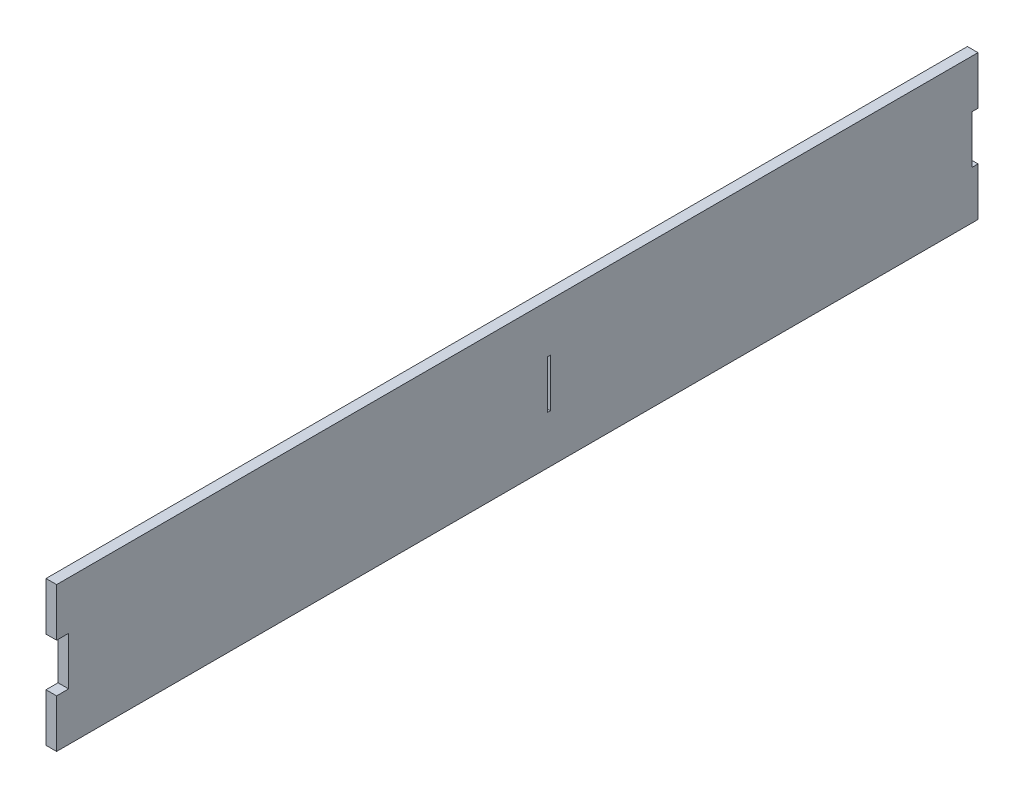
SolidWorks part; units mm, degrees
material "Balsa"
ref_plane "Front Plane" through (0, 0, 0) normal (0, 0, 1) x (1, 0, 0)
ref_plane "Top Plane" through (0, 0, 0) normal (0, 1, 0) x (1, 0, 0)
ref_plane "Right Plane" through (0, 0, 0) normal (1, 0, 0) x (0, 0, -1)
ref_plane "Plane1" through (-94.488, 0, 0) normal (-1, 0, 0) x (0, -1, 0)
sketch "Sketch1" plane through (-94.488, 0, 0) normal (-1, 0, 0) x (0, -1, 0)
  line L0 (111.125, -457.2) -> (85.725, -457.2)
  line L1 (85.725, -457.2) -> (85.725, -455.6125)
  line L2 (85.725, -455.6125) -> (111.125, -455.6125)
  line L3 (111.125, -455.6125) -> (111.125, -457.2)
  line L4 (111.125, -203.2) -> (85.725, -203.2)
  line L5 (85.725, -203.2) -> (85.725, -196.85)
  line L6 (85.725, -196.85) -> (60.325, -196.85)
  line L7 (60.325, -196.85) -> (60.325, -682.625)
  line L8 (60.325, -682.625) -> (85.725, -682.625)
  line L9 (85.725, -682.625) -> (85.725, -679.45)
  line L10 (85.725, -679.45) -> (111.125, -679.45)
  line L11 (111.125, -679.45) -> (111.125, -682.625)
  line L12 (111.125, -682.625) -> (136.525, -682.625)
  line L13 (136.525, -682.625) -> (136.525, -196.85)
  line L14 (136.525, -196.85) -> (111.125, -196.85)
  line L15 (111.125, -196.85) -> (111.125, -203.2)
  line L16 (136.525, -196.85) -> (185.6232, -196.85) construction
  line L17 (185.6232, -196.85) -> (185.6232, -227.7965) construction
  line L18 (184.1182, -229.5729) -> (139.535, -282.1971)
  line L19 (136.525, -203.2) -> (149.225, -203.2)
  line L20 (149.225, -203.2) -> (149.225, -196.85)
  line L21 (168.275, -196.85) -> (168.275, -203.2)
  line L22 (168.275, -203.2) -> (185.6232, -203.2)
  line L23 (185.6232, -203.2) -> (185.6232, -225.4683)
  line L24 (168.275, -196.85) -> (149.225, -196.85)
  line L25 (136.525, -679.45) -> (146.05, -679.45)
  line L26 (146.05, -679.45) -> (146.05, -684.2125)
  line L27 (146.05, -684.2125) -> (161.925, -684.2125)
  line L28 (161.925, -684.2125) -> (161.925, -679.45)
  line L29 (161.925, -679.45) -> (171.45, -679.45)
  line L30 (171.45, -679.45) -> (171.45, -665.4434)
  line L31 (170.5993, -662.2684) -> (138.2265, -606.197)
  circle A0 centre (130.175, -666.75) radius 1.7526 construction
  circle A1 centre (130.175, -615.95) radius 1.7526 construction
  circle A2 centre (130.175, -565.15) radius 1.7526 construction
  circle A3 centre (130.175, -514.35) radius 1.7526 construction
  circle A4 centre (130.175, -463.55) radius 1.7526 construction
  circle A5 centre (130.175, -412.75) radius 1.7526 construction
  circle A6 centre (130.175, -361.95) radius 1.7526 construction
  circle A7 centre (130.175, -311.15) radius 1.7526 construction
  circle A8 centre (130.175, -260.35) radius 1.7526 construction
  circle A9 centre (130.175, -209.55) radius 1.7526 construction
  arc A10 (184.1182, -229.5729) -> (185.6232, -225.4683) centre (179.2732, -225.4683) ccw
  arc A11 (139.535, -282.1971) -> (136.525, -290.4065) centre (149.225, -290.4065) ccw
  arc A12 (136.525, -599.847) -> (138.2265, -606.197) centre (149.225, -599.847) ccw
  arc A13 (171.45, -665.4434) -> (170.5993, -662.2684) centre (165.1, -665.4434) ccw
  point P38 (136.525, -285.75)
  point P58 (136.525, -603.25)
  dimension "D14" = 12.7
  dimension "D15" = 6.35
  dimension "D21" = 12.7
  dimension "D22" = 6.35
  dimension "D1" = 222.25
  dimension "D2" = 485.775
  dimension "D3" = 76.2
  dimension "D4" = 3.175
  dimension "D5" = 6.35
  dimension "D6" = 25.4
  dimension "D7" = 25.4
  dimension "D8" = 1.5875
  dimension "D9" = 49.0982
  dimension "D10" = 82.55
  dimension "D11" = 40.271
  dimension "D12" = 19.05
  dimension "D13" = 12.7
  dimension "D16" = 9.525
  dimension "D17" = 34.925
  dimension "D18" = 15.875
  dimension "D19" = 30
  dimension "D20" = 76.2
  dimension "D23" = 4.7625
extrude "Boss-Extrude1" add sketch "Sketch1" against normal blind 5.588
sketch "Sketch2" plane through (-88.9, 0, 0) normal (1, 0, 0) x (0, 0, -1)
  line L1 (168.3165, -136.525) -> (713.9508, -136.525)
  line L2 (168.3165, -136.525) -> (168.3165, -205.2234)
  line L3 (168.3165, -205.2234) -> (713.9508, -205.2234)
  line L4 (713.9508, -136.525) -> (713.9508, -205.2234)
extrude "Cut-Extrude1" cut sketch "Sketch2" against normal blind 7.62
